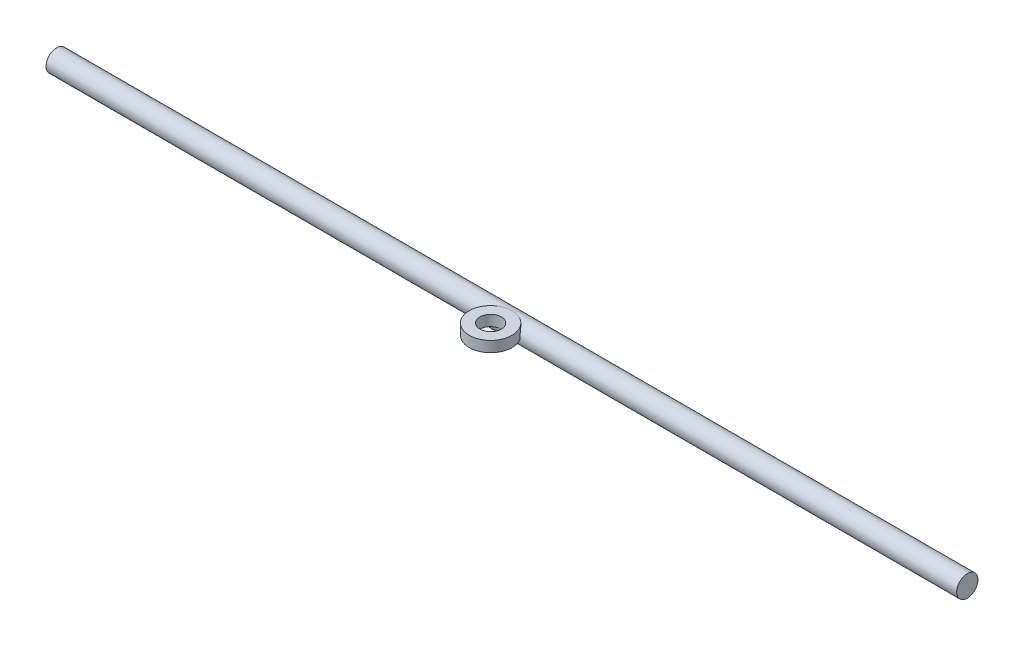
SolidWorks part; units mm, degrees
ref_plane "Plan de face" through (0, 0, 0) normal (0, 0, 1) x (1, 0, 0)
ref_plane "Plan de dessus" through (0, 0, 0) normal (0, 1, 0) x (1, 0, 0)
ref_plane "Plan de droite" through (0, 0, 0) normal (1, 0, 0) x (0, 0, -1)
sketch "Esquisse1" plane through (0, 0, 0) normal (0, 0, 1) x (1, 0, 0)
  line L0 (-213.3333, 0) -> (213.3333, 0)
  dimension "D1" = 426.6667
sweep "Balayage1" add path "Esquisse1" circular profile diameter 10 parameters "D3"=10
sketch "Esquisse2" plane through (0, 0, 0) normal (0, 1, 0) x (1, 0, 0)
  line L0 (-213.3333, -5) -> (213.3333, -5) construction
  circle A0 centre (0, -10) radius 5
  circle A1 centre (0, -10) radius 10
  dimension "D1" = 10
  dimension "D2" = 5
extrude "Boss.-Extru.1" add sketch "Esquisse2" along normal blind 5
